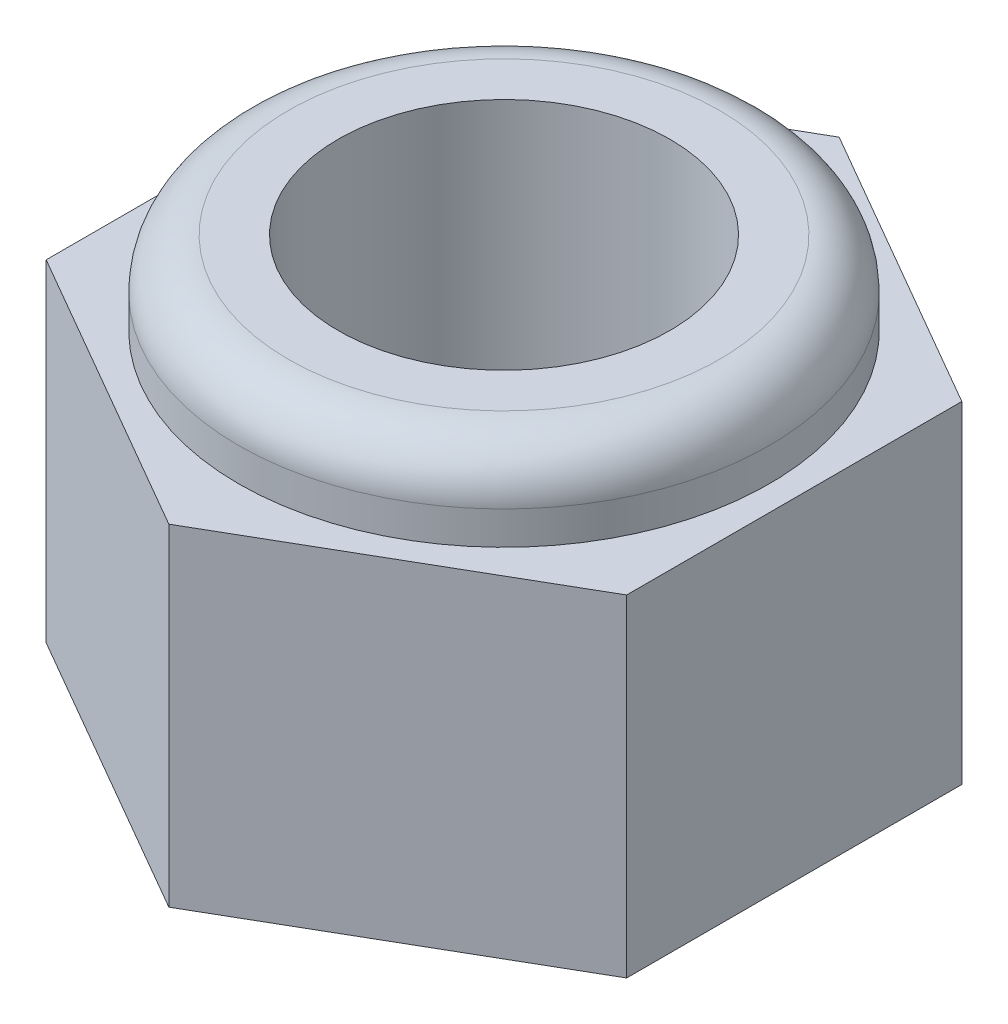
SolidWorks part; units mm, degrees
ref_plane "Front Plane" through (0, 0, 0) normal (0, 0, 1) x (1, 0, 0)
ref_plane "Top Plane" through (0, 0, 0) normal (0, 1, 0) x (1, 0, 0)
ref_plane "Right Plane" through (0, 0, 0) normal (1, 0, 0) x (0, 0, -1)
sketch "Sketch1" plane through (0, 0, 0) normal (0, 1, 0) x (1, 0, 0)
  line L1 (0, 4.0415) -> (-3.5, 2.0207)
  line L2 (-3.5, 2.0207) -> (-3.5, -2.0207)
  line L3 (-3.5, -2.0207) -> (0, -4.0415)
  line L4 (0, -4.0415) -> (3.5, -2.0207)
  line L5 (3.5, -2.0207) -> (3.5, 2.0207)
  line L6 (3.5, 2.0207) -> (0, 4.0415)
  circle A0 centre (0, 0) radius 3.5 construction
  dimension "D1" = 7
extrude "Boss-Extrude1" add sketch "Sketch1" along normal blind 4
sketch "Sketch2" plane through (0, 0, 0) normal (0, 0, 1) x (1, 0, 0)
  line L0 (0, 0) -> (0, 9.1057) construction
  line L1 (0, 5) -> (2.6, 5)
  line L2 (-3.5, 0) -> (0, 0) construction
  line L3 (0, 4) -> (-3.5, 4) construction
  line L4 (-3.5, 4) -> (-3.5, 0) construction
  line L5 (0, 0) -> (3.5, 0) construction
  line L6 (3.5, 0) -> (3.5, 4) construction
  line L7 (3.5, 4) -> (0, 4) construction
  line L8 (-3.5, 0) -> (0, 0)
  line L9 (0, 4) -> (-3.5, 4)
  line L10 (-3.5, 4) -> (-3.5, 0)
  line L11 (0, 0) -> (3.5, 0)
  line L12 (3.5, 0) -> (3.5, 4)
  line L13 (3.5, 4) -> (0, 4)
  line L14 (3.2, 4.4) -> (3.2, 4)
  arc A0 (2.6, 5) -> (3.2, 4.4) centre (2.6, 4.4) cw
  dimension "D1" = 0.6
  dimension "D2" = 3.2
  dimension "D3" = 1
revolve "Revolve1" add sketch "Sketch2" angle 360 about L0
sketch "Sketch4" plane through (0, 0, 0) normal (0, -1, 0) x (1, 0, 0)
  circle A0 centre (0, 0) radius 2
  dimension "D1" = 4
extrude "Cut-Extrude1" cut sketch "Sketch4" against normal up to next
